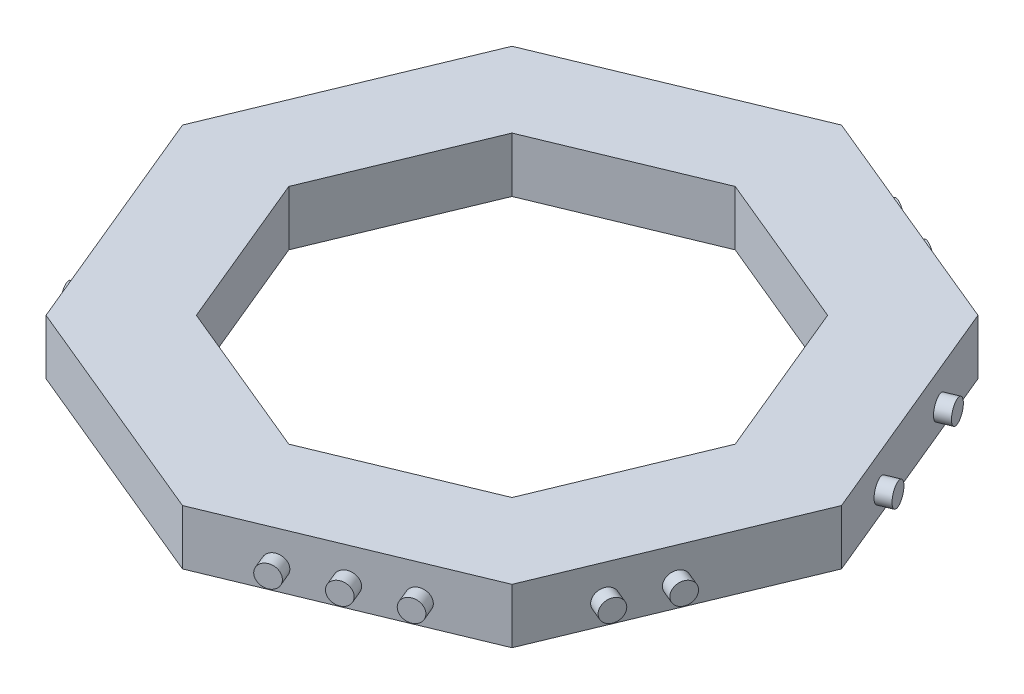
SolidWorks part; units mm, degrees
ref_plane "Front Plane" through (0, 0, 0) normal (0, 0, 1) x (1, 0, 0)
ref_plane "Top Plane" through (0, 0, 0) normal (0, 1, 0) x (1, 0, 0)
ref_plane "Right Plane" through (0, 0, 0) normal (1, 0, 0) x (0, 0, -1)
sketch "Sketch3" plane through (0, 0, 0) normal (0, 1, 0) x (1, 0, 0)
  line L1 (30, 0) -> (21.2132, 21.2132)
  line L2 (21.2132, 21.2132) -> (0, 30)
  line L3 (0, 30) -> (-21.2132, 21.2132)
  line L4 (-21.2132, 21.2132) -> (-30, 0)
  line L5 (-30, 0) -> (-21.2132, -21.2132)
  line L6 (-21.2132, -21.2132) -> (0, -30)
  line L7 (0, -30) -> (21.2132, -21.2132)
  line L8 (21.2132, -21.2132) -> (30, 0)
  circle A0 centre (0, 0) radius 27.7164 construction
  dimension "D1" = 30
extrude "Boss-Extrude1" add sketch "Sketch3" along normal blind 5
sketch "Sketch5" plane through (0, 5, 0) normal (0, 1, 0) x (1, 0, 0)
  line L1 (20.32, 0) -> (14.3684, 14.3684)
  line L2 (14.3684, 14.3684) -> (0, 20.32)
  line L3 (0, 20.32) -> (-14.3684, 14.3684)
  line L4 (-14.3684, 14.3684) -> (-20.32, 0)
  line L5 (-20.32, 0) -> (-14.3684, -14.3684)
  line L6 (-14.3684, -14.3684) -> (0, -20.32)
  line L7 (0, -20.32) -> (14.3684, -14.3684)
  line L8 (14.3684, -14.3684) -> (20.32, 0)
  circle A0 centre (0, 0) radius 18.7732 construction
  dimension "D1" = 20.32
extrude "Cut-Extrude1" cut sketch "Sketch5" against normal blind 5
sketch "Sketch6" plane through (10.6066, 0, 25.6066) normal (0.3827, 0, 0.9239) x (0.9239, 0, -0.3827)
  circle A0 centre (0, 2) radius 1
  circle A1 centre (-5, 2) radius 1
  circle A2 centre (5, 2) radius 1
sketch "Sketch7" plane through (-25.6066, 0, 10.6066) normal (-0.9239, 0, 0.3827) x (0.3827, 0, 0.9239)
  circle A0 centre (5, 2) radius 1
sketch "Sketch8" plane through (-25.6066, 0, -10.6066) normal (-0.9239, 0, -0.3827) x (-0.3827, 0, 0.9239)
  circle A0 centre (0, 2) radius 1
sketch "Sketch9" plane through (-10.6066, 0, -25.6066) normal (-0.3827, 0, -0.9239) x (-0.9239, 0, 0.3827)
  circle A0 centre (-5, 2) radius 1
sketch "Sketch10" plane through (10.6066, 0, -25.6066) normal (0.3827, 0, -0.9239) x (-0.9239, 0, -0.3827)
  circle A0 centre (0, 2) radius 1
  circle A1 centre (5, 2) radius 1
sketch "Sketch11" plane through (25.6066, 0, -10.6066) normal (0.9239, 0, -0.3827) x (-0.3827, 0, -0.9239)
  circle A0 centre (5, 2) radius 1
  circle A1 centre (-5, 2) radius 1
sketch "Sketch12" plane through (25.6066, 0, 10.6066) normal (0.9239, 0, 0.3827) x (0.3827, 0, -0.9239)
  circle A0 centre (0, 2) radius 1
  circle A1 centre (-5, 2) radius 1
extrude "Boss-Extrude5" add sketch "Sketch6" along normal blind 1.25 contours A2 | A1 | A0
extrude "Boss-Extrude6" add sketch "Sketch7" along normal blind 1.25 contours A0
extrude "Boss-Extrude7" add sketch "Sketch8" along normal blind 1.25 contours A0
extrude "Boss-Extrude8" add sketch "Sketch9" along normal blind 1.25 contours A0
extrude "Boss-Extrude9" add sketch "Sketch10" along normal blind 1.25 contours A0 | A1
extrude "Boss-Extrude10" add sketch "Sketch11" along normal blind 1.25 contours A1 | A0
extrude "Boss-Extrude11" add sketch "Sketch12" along normal blind 1.25 contours A1 | A0
